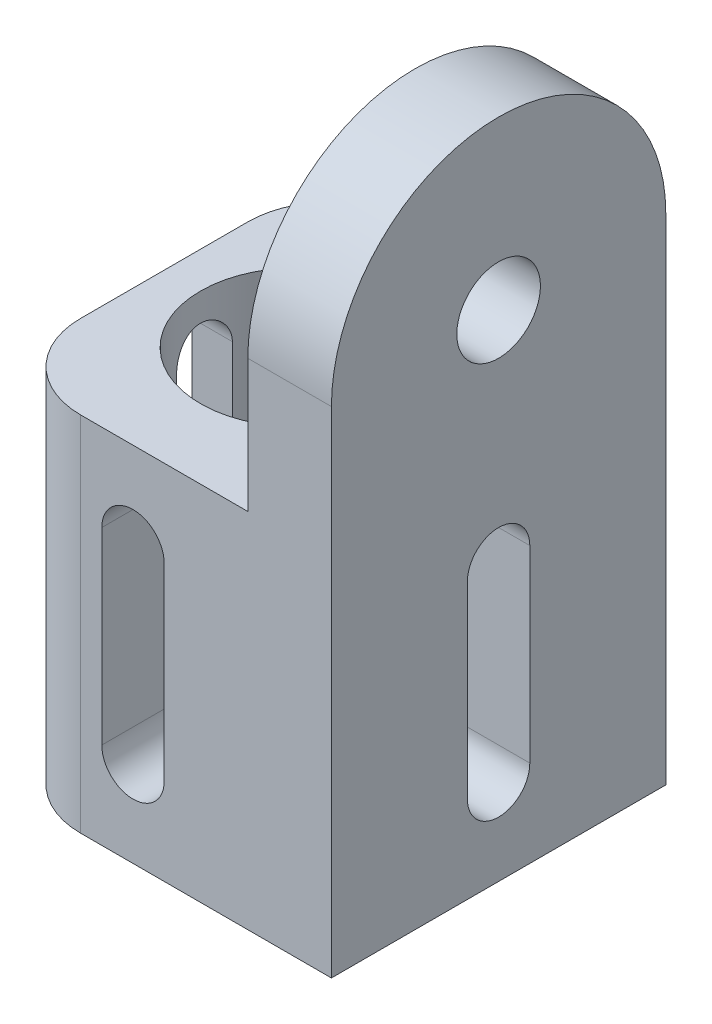
SolidWorks part; units mm, degrees
material "6061-T6 (SS)"
ref_plane "Front" through (0, 0, 0) normal (0, 0, 1) x (1, 0, 0)
ref_plane "Top" through (0, 0, 0) normal (0, 1, 0) x (1, 0, 0)
ref_plane "Right" through (0, 0, 0) normal (1, 0, 0) x (0, 0, -1)
sketch "Sketch1" plane through (0, 0, 0) normal (0, 0, 1) x (1, 0, 0)
  line L0 (0, 0) -> (0, 150.876)
  line L1 (0, 150.876) -> (-19.05, 150.876)
  line L2 (-19.05, 150.876) -> (-19.05, 82.55)
  line L3 (-19.05, 82.55) -> (-76.2, 82.55)
  line L4 (-76.2, 82.55) -> (-76.2, 0)
  line L5 (-76.2, 0) -> (0, 0)
  dimension "D1" = 76.2
  dimension "D2" = 150.876
  dimension "D3" = 82.55
  dimension "D4" = 19.05
extrude "Boss-Extrude1" add sketch "Sketch1" along normal mid plane 76.2
sketch "Sketch2" plane through (0, 0, 38.1) normal (0, 0, 1) x (1, 0, 0)
  line L0 (-45.212, 62.738) -> (-45.212, 19.812) construction
  line L1 (-38.1, 62.738) -> (-38.1, 19.812)
  line L2 (-52.324, 62.738) -> (-52.324, 19.812)
  line L3 (-76.2, 0) -> (0, 0) construction
  line L4 (-76.2, 82.55) -> (-76.2, 0) construction
  arc A0 (-38.1, 62.738) -> (-52.324, 62.738) centre (-45.212, 62.738) ccw
  arc A1 (-52.324, 19.812) -> (-38.1, 19.812) centre (-45.212, 19.812) ccw
  point P2 (-45.212, 41.275)
  dimension "D2" = 14.224
  dimension "D1" = 42.926
  dimension "D3" = 19.812
  dimension "D4" = 30.988
extrude "Cut-Extrude1" cut sketch "Sketch2" against normal through all
sketch "Sketch3" plane through (-76.2, 0, 0) normal (-1, 0, 0) x (0, 0, 1)
  line L0 (0, 69.85) -> (0, 25.4) construction
  line L1 (6.35, 69.85) -> (6.35, 25.4)
  line L2 (-6.35, 69.85) -> (-6.35, 25.4)
  line L3 (38.1, 0) -> (-38.1, 0) construction
  arc A0 (6.35, 69.85) -> (-6.35, 69.85) centre (0, 69.85) ccw
  arc A1 (-6.35, 25.4) -> (6.35, 25.4) centre (0, 25.4) ccw
  point P3 (0, 47.625)
  dimension "D1" = 44.45
  dimension "D2" = 12.7
  dimension "D3" = 25.4
extrude "Cut-Extrude2" cut sketch "Sketch3" against normal blind 30.988
sketch "Sketch4" plane through (0, 0, 0) normal (1, 0, 0) x (0, 0, -1)
  line L0 (0, 19.812) -> (0, 62.738) construction
  line L1 (-7.112, 19.812) -> (-7.112, 62.738)
  line L2 (7.112, 19.812) -> (7.112, 62.738)
  line L4 (-38.1, 0) -> (38.1, 0) construction
  arc A0 (-7.112, 19.812) -> (7.112, 19.812) centre (0, 19.812) ccw
  arc A1 (7.112, 62.738) -> (-7.112, 62.738) centre (0, 62.738) ccw
  point P3 (0, 41.275)
  dimension "D1" = 14.224
  dimension "D2" = 42.926
  dimension "D3" = 19.812
extrude "Cut-Extrude3" cut sketch "Sketch4" against normal blind 38.1
sketch "Sketch5" plane through (0, 82.55, 0) normal (0, 1, 0) x (1, 0, 0)
  line L0 (-76.2, -38.1) -> (-76.2, 38.1) construction
  line L1 (-76.2, 0) -> (-45.72, 0) construction
  circle A0 centre (-45.72, 0) radius 22.225
  dimension "D1" = 44.45
  dimension "D2" = 30.48
extrude "Cut-Extrude4" cut sketch "Sketch5" against normal blind 69.85
sketch "Sketch6" plane through (-19.05, 0, 0) normal (-1, 0, 0) x (0, 0, 1)
  line L0 (-38.1, 150.876) -> (-38.1, 82.55) construction
  line L1 (38.1, 150.876) -> (38.1, 82.55) construction
  line L2 (38.1, 150.876) -> (-38.1, 150.876) construction
  line L3 (-38.1, 112.776) -> (-38.1, 150.876)
  line L4 (-38.1, 150.876) -> (38.1, 150.876)
  line L5 (38.1, 150.876) -> (38.1, 112.776)
  arc A0 (-38.1, 112.776) -> (38.1, 112.776) centre (0, 112.776) cw
  line M1 (-38.1, 150.876) -> (-38.1, 82.55)
  line M3 (38.1, 82.55) -> (38.1, 150.876)
  line M4 (38.1, 150.876) -> (-38.1, 150.876)
extrude "Cut-Extrude5" cut sketch "Sketch6" against normal through all contours A0 L4 M1 | A0 M4 M3
hole_wizard "3/4 (0.75) Diameter Hole1" positions "Sketch7" profile "Sketch8" hole size "3/4" standard "ANSI Inch" end condition through all
sketch "Sketch7" plane through (-19.05, 0, 0) normal (-1, 0, 0) x (0, 0, 1)
  point P0 (0, 112.776)
sketch "Sketch8" plane through (-19.05, 112.776, 0) normal (0, 1, 0) x (0, 0, 1)
  line L0 (0, 0) -> (0, 19.05)
  line L1 (0, 19.05) -> (9.525, 19.05)
  line L2 (9.525, 19.05) -> (9.525, 0)
  line L5 (9.525, 0) -> (0, 0)
  line L11 (0, -6.35) -> (0, 107.95) construction
  dimension "Thru Hole Dia." = 19.05
  dimension "Thru Hole Depth" = 19.05
fillet "Fillet1" radius 19.05 2 edges at (-76.2, 41.275, 38.1) (-76.2, 41.275, -38.1)
